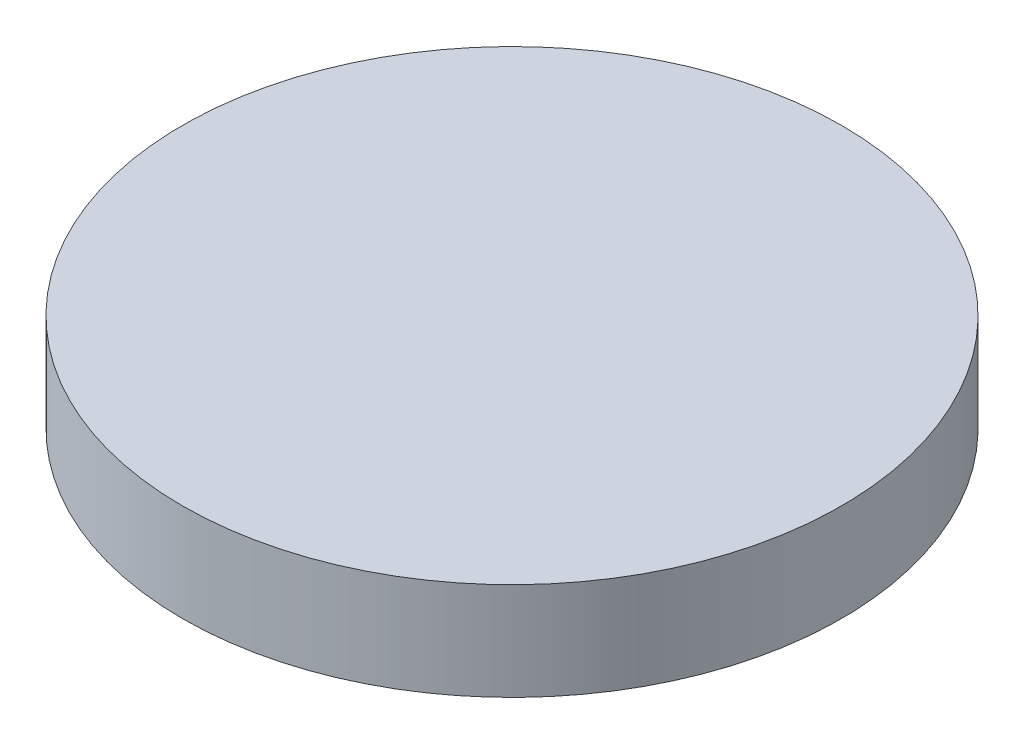
SolidWorks part; units mm, degrees
ref_plane "Front Plane" through (0, 0, 0) normal (0, 0, 1) x (1, 0, 0)
ref_plane "Top Plane" through (0, 0, 0) normal (0, 1, 0) x (1, 0, 0)
ref_plane "Right Plane" through (0, 0, 0) normal (1, 0, 0) x (0, 0, -1)
sketch "Sketch1" plane through (0, 0, 0) normal (0, 1, 0) x (1, 0, 0)
  circle A0 centre (0, 0) radius 27
  dimension "D1" = 54
extrude "Boss-Extrude1" add sketch "Sketch1" along normal blind 8
